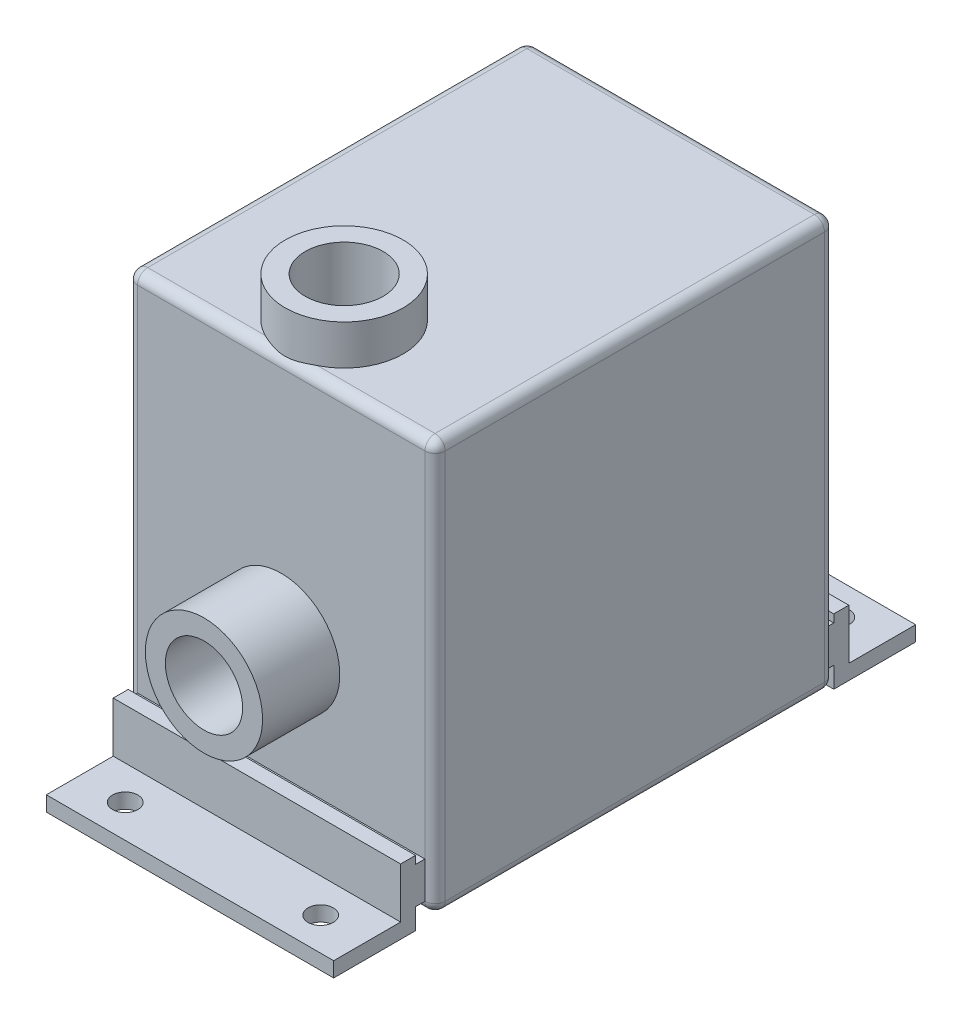
SolidWorks part; units mm, degrees
ref_plane "Front Plane" through (0, 0, 0) normal (0, 0, 1) x (1, 0, 0)
ref_plane "Top Plane" through (0, 0, 0) normal (0, 1, 0) x (1, 0, 0)
ref_plane "Right Plane" through (0, 0, 0) normal (1, 0, 0) x (0, 0, -1)
sketch "Sketch1" plane through (0, 0, 0) normal (0, 1, 0) x (1, 0, 0)
  line L1 (-23.1, 30) -> (23.1, 30)
  line L2 (-23.1, 30) -> (-23.1, -30)
  line L3 (-23.1, -30) -> (23.1, -30)
  line L4 (23.1, 30) -> (23.1, -30)
  line L5 (-23.1, 30) -> (23.1, -30) construction
  line L6 (-23.1, -30) -> (23.1, 30) construction
  point P0 (0, 0)
  dimension "D1" = 46.2
  dimension "D2" = 60
extrude "Boss-Extrude1" add sketch "Sketch1" along normal mid plane 61.6
fillet "Fillet1" radius 1.524 12 edges at (-23.1, -30.8, 0) (-23.1, 0, -30) (0, -30.8, -30) (23.1, 0, -30) (23.1, -30.8, 0) (-23.1, 0, 30) (23.1, 0, 30) (0, -30.8, 30) (0, 30.8, 30) (-23.1, 30.8, 0) (0, 30.8, -30) (23.1, 30.8, 0)
sketch "Sketch2" plane through (0, 30.8, 0) normal (0, 1, 0) x (1, 0, 0)
  circle A0 centre (0, -20.5455) radius 8.85
  dimension "D1" = 17.7
  dimension "D2" = 20.5455
extrude "Boss-Extrude2" add sketch "Sketch2" along normal blind 6 and the other way blind 12.07
sketch "Sketch3" plane through (0, 36.8, 0) normal (0, 1, 0) x (1, 0, 0)
  circle A0 centre (0, -20.5455) radius 5.85
  circle A1 centre (0, -20.5455) radius 8.85 construction
  dimension "D1" = 3
extrude "Cut-Extrude1" cut sketch "Sketch3" against normal blind 35.464
sketch "Sketch4" plane through (0, 0, 30) normal (0, 0, 1) x (1, 0, 0)
  line L0 (3.928, 30.8) -> (21.576, 30.8) construction
  circle A0 centre (0, -6.2) radius 8.8
  dimension "D1" = 17.6
  dimension "D2" = 37
extrude "Boss-Extrude3" add sketch "Sketch4" along normal blind 11.6
sketch "Sketch5" plane through (0, 0, 41.6) normal (0, 0, 1) x (1, 0, 0)
  circle A0 centre (0, -6.2) radius 5.8
  circle A1 centre (0, -6.2) radius 8.8 construction
  dimension "D1" = 3
extrude "Cut-Extrude2" cut sketch "Sketch5" against normal blind 59.86
sketch "Sketch6" plane through (0, 0, 30) normal (0, 0, 1) x (1, 0, 0)
  line L0 (21.576, -29.276) -> (21.576, 29.276) construction
  line L1 (-21.576, -29.276) -> (21.576, -29.276)
  line L2 (-21.576, -29.276) -> (-21.576, -23.776)
  line L3 (-21.576, -23.776) -> (21.576, -23.776)
  line L4 (21.576, -29.276) -> (21.576, -23.776)
  dimension "D1" = 5.5
extrude "Boss-Extrude4" add sketch "Sketch6" along normal blind 1.4
sketch "Sketch8" plane through (-21.576, 0, 0) normal (-1, 0, 0) x (0, 0, 1)
  line L0 (31.4, -32.4) -> (31.4, -22.5955)
  line L1 (31.4, -22.5955) -> (33.65, -22.5955)
  line L2 (33.65, -22.5955) -> (33.65, -30.15)
  line L3 (33.65, -30.15) -> (43.7, -30.15)
  line L4 (43.7, -30.15) -> (43.7, -32.4)
  line L5 (43.7, -32.4) -> (31.4, -32.4)
  line L6 (31.4, -23.776) -> (31.4, -29.276) construction
  line L7 (31.4, -23.776) -> (30, -23.776) construction
  line L8 (28.476, -30.8) -> (-28.476, -30.8) construction
  dimension "D1" = 1.1805
  dimension "D2" = 2.25
  dimension "D3" = 2.25
  dimension "D4" = 1.6
  dimension "D5" = 12.3
extrude "Boss-Extrude5" add sketch "Sketch8" against normal up to surface (43.152 mm away) up to face at (21.576, -26.526, 30.7)
mirror "Mirror1" about plane through (0, 0, 0) normal (0, 0, 1) of "Boss-Extrude5", "Boss-Extrude4"
sketch "Sketch9" plane through (0, -32.4, 0) normal (0, -1, 0) x (1, 0, 0)
  line L1 (-14.675, 38.75) -> (14.675, 38.75) construction
  line L2 (-14.675, 38.75) -> (-14.675, -38.75) construction
  line L3 (-14.675, -38.75) -> (14.675, -38.75) construction
  line L4 (14.675, 38.75) -> (14.675, -38.75) construction
  line L5 (-14.675, 38.75) -> (14.675, -38.75) construction
  line L6 (-14.675, -38.75) -> (14.675, 38.75) construction
  circle A0 centre (-14.675, 38.75) radius 1.9
  circle A1 centre (14.675, 38.75) radius 1.9
  circle A2 centre (14.675, -38.75) radius 1.9
  circle A3 centre (-14.675, -38.75) radius 1.9
  point P0 (0, 0)
  dimension "D1" = 3.8
  dimension "D2" = 29.35
  dimension "D3" = 77.5
extrude "Cut-Extrude3" cut sketch "Sketch9" against normal blind 14.1
